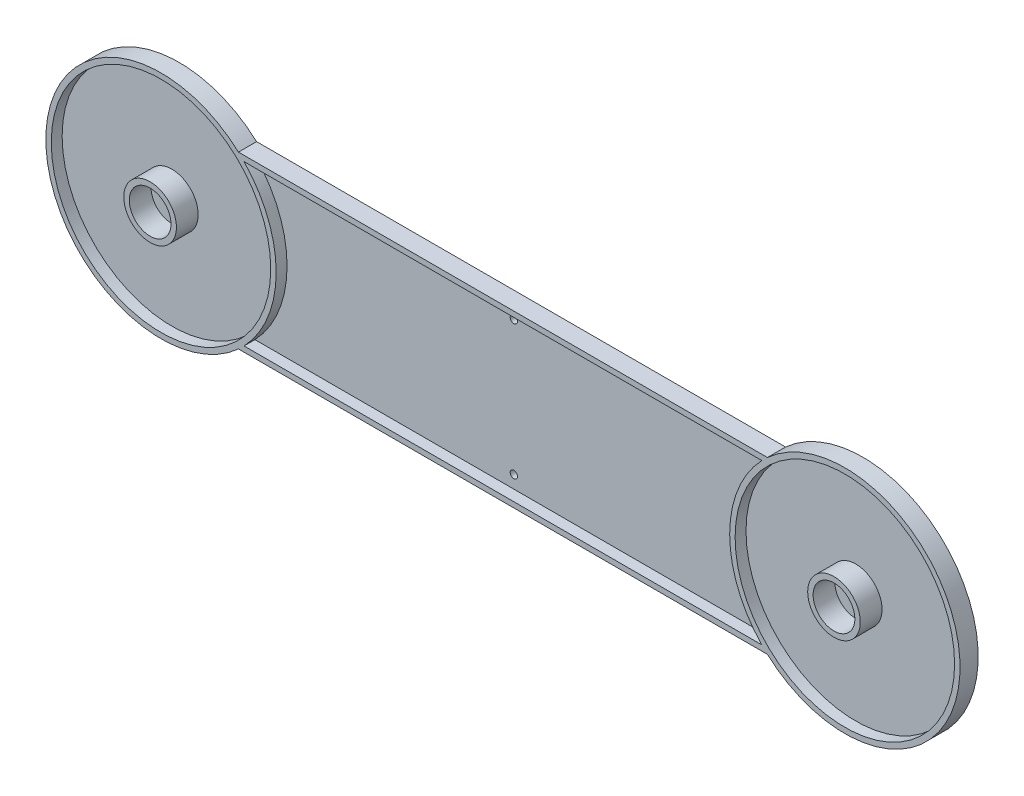
SolidWorks part; units mm, degrees
material "Chrome Stainless Steel"
ref_plane "Front Plane" through (0, 0, 0) normal (0, 0, 1) x (1, 0, 0)
ref_plane "Top Plane" through (0, 0, 0) normal (0, 1, 0) x (1, 0, 0)
ref_plane "Right Plane" through (0, 0, 0) normal (1, 0, 0) x (0, 0, -1)
sketch "Sketch1" plane through (0, 0, 0) normal (0, 0, 1) x (1, 0, 0)
  line L1 (72.9002, -23.5) -> (-72.9002, -23.5)
  line L3 (72.9002, 23.5) -> (-72.9002, 23.5)
  line L5 (44.1131, -23.5) -> (-44.1131, 23.5) construction
  line L6 (44.1131, 23.5) -> (-44.1131, -23.5) construction
  arc A0 (-72.9002, 23.5) -> (-72.9002, -23.5) centre (-94.25, 0) ccw
  arc A1 (72.9002, -23.5) -> (72.9002, 23.5) centre (94.25, 0) ccw
  point P4 (0, 0)
  dimension "D1" = 63.5
  dimension "D2" = 63.5
  dimension "D3" = 188.5
  dimension "D4" = 94.25
  dimension "D5" = 23.5
extrude "Boss-Extrude1" add sketch "Sketch1" along normal blind 2
sketch "Sketch2" plane through (0, 0, 2) normal (0, 0, 1) x (1, 0, 0)
  line L0 (-71.3576, -22) -> (71.3576, -22)
  line L1 (71.3576, 22) -> (-71.3576, 22)
  line L2 (-72.9002, -23.5) -> (72.9002, -23.5)
  line L3 (72.9002, 23.5) -> (-72.9002, 23.5)
  line L4 (-72.9002, -23.5) -> (72.9002, -23.5)
  line L5 (72.9002, 23.5) -> (-72.9002, 23.5)
  line L6 (0, -55) -> (0, 55) construction
  line L8 (73.488, 22) -> (-73.488, 22) construction
  line L9 (-73.488, -22) -> (73.488, -22) construction
  arc A0 (-73.488, 22) -> (-73.488, -22) centre (-94.25, 0) ccw
  arc A1 (73.488, -22) -> (73.488, 22) centre (94.25, 0) ccw
  arc A2 (-72.9002, 23.5) -> (-72.9002, -23.5) centre (-94.25, 0) ccw
  arc A3 (72.9002, -23.5) -> (72.9002, 23.5) centre (94.25, 0) ccw
  arc A4 (-72.9002, 23.5) -> (-72.9002, -23.5) centre (-94.25, 0) ccw
  arc A5 (72.9002, -23.5) -> (72.9002, 23.5) centre (94.25, 0) ccw
  circle A6 centre (-94.25, 0) radius 30.25
  arc A7 (-72.9002, 23.5) -> (-72.9002, -23.5) centre (-94.25, 0) ccw
  circle A8 centre (94.25, 0) radius 30.25
  arc A9 (73.488, 22) -> (73.488, -22) centre (94.25, 0) cw
  arc A10 (72.9002, 23.5) -> (72.9002, -23.5) centre (94.25, 0) cw
  arc A11 (-71.3576, -22) -> (-71.3576, 22) centre (-94.25, 0) ccw
  arc A12 (71.3576, -22) -> (71.3576, 22) centre (94.25, 0) cw
  arc M15 (-72.9002, 23.5) -> (-72.9002, -23.5) centre (-94.25, 0) ccw
  line M16 (-72.9002, -23.5) -> (72.9002, -23.5)
  arc M17 (72.9002, -23.5) -> (72.9002, 23.5) centre (94.25, 0) ccw
  line M18 (72.9002, 23.5) -> (-72.9002, 23.5)
  dimension "D1" = 0
  dimension "D2" = 1.5
extrude "Boss-Extrude2" add sketch "Sketch2" along normal blind 3 contours A12 L0 A11 L1 A6 A0 A1 A8 M18 M15 M16 M17
sketch "Sketch3" plane through (0, 0, 2) normal (0, 0, 1) x (1, 0, 0)
  line L0 (-72.9002, -23.5) -> (72.9002, -23.5) construction
  line L1 (72.9002, 23.5) -> (-72.9002, 23.5) construction
  circle A0 centre (0, -18.5) radius 1
  circle A1 centre (0, 18.5) radius 1
  dimension "D1" = 2
  dimension "D2" = 2
  dimension "D3" = 5
  dimension "D4" = 5
extrude "Cut-Extrude1" cut sketch "Sketch3" against normal through all both and the other way through all
sketch "Sketch4" plane through (0, 0, 2) normal (0, 0, 1) x (1, 0, 0)
  circle A0 centre (-94.25, 0) radius 7.25
  circle A1 centre (-94.25, 0) radius 5.75
  dimension "D1" = 14.5
  dimension "D3" = 11.5
extrude "Boss-Extrude3" add sketch "Sketch4" along normal blind 6
mirror "Mirror1" about plane through (0, 0, 0) normal (1, 0, 0) of "Boss-Extrude3"
